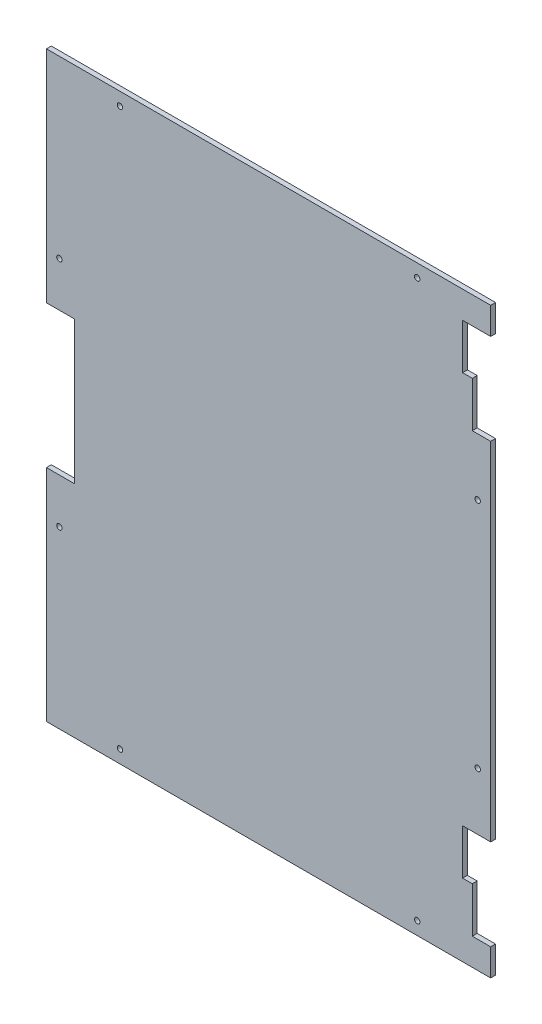
SolidWorks part; units mm, degrees
ref_plane "Front Plane" through (0, 0, 0) normal (0, 0, 1) x (1, 0, 0)
ref_plane "Top Plane" through (0, 0, 0) normal (0, 1, 0) x (1, 0, 0)
ref_plane "Right Plane" through (0, 0, 0) normal (1, 0, 0) x (0, 0, -1)
sketch "Sketch1" plane through (0, 0, 0) normal (0, 0, 1) x (1, 0, 0)
  line L16 (-206.5, 269.5) -> (204.5, 269.5)
  line L32 (-206.5, 269.5) -> (-206.5, 244.5)
  line L33 (-206.5, -269.5) -> (204.5, -269.5)
  line L42 (204.5, 160.5) -> (204.5, -160.5)
  line L43 (-206.5, 0) -> (204.5, 0) construction
  line L49 (204.5, 269.5) -> (204.5, 244.5)
  line L50 (204.5, -244.5) -> (204.5, -269.5)
  line L51 (-1, 269.5) -> (-1, -269.5) construction
  line L57 (-206.5, 160.5) -> (-206.5, 66)
  line L63 (-206.5, -244.5) -> (-206.5, -269.5)
  line L64 (-206.5, -66) -> (-206.5, -160.5)
  line L65 (-206.5, 66) -> (-180.5, 66)
  line L67 (-206.5, -66) -> (-180.5, -66)
  line L68 (-180.5, 66) -> (-180.5, -66)
  line L70 (204.5, 160.5) -> (187.5, 160.5)
  line L71 (187.5, 202.5) -> (187.5, 160.5)
  line L72 (178.5, 202.5) -> (178.5, 244.5)
  line L73 (204.5, 244.5) -> (178.5, 244.5)
  line L74 (178.5, 202.5) -> (187.5, 202.5)
  line L75 (187.5, -244.5) -> (204.5, -244.5)
  line L76 (187.5, -202.5) -> (187.5, -244.5)
  line L77 (178.5, -202.5) -> (187.5, -202.5)
  line L78 (178.5, -160.5) -> (178.5, -202.5)
  line L79 (204.5, -160.5) -> (178.5, -160.5)
  line L80 (-206.5, 160.5) -> (-206.5, 244.5)
  line L81 (-206.5, -160.5) -> (-206.5, -244.5)
  circle A0 centre (136.5, -257.5) radius 2.5
  circle A3 centre (-138.5, -257.5) radius 2.5
  circle A4 centre (-138.5, 257.5) radius 2.5
  circle A7 centre (136.5, 257.5) radius 2.5
  circle A8 centre (-194.5, 107.5) radius 2.5
  circle A9 centre (-194.5, -107.5) radius 2.5
  circle A10 centre (192.5, 107.5) radius 2.5
  circle A11 centre (192.5, -107.5) radius 2.5
  point P17 (185.5, -200.5)
  dimension "D5" = 25
  dimension "D3" = 206.5
  dimension "D7" = 12
  dimension "D10" = 12
  dimension "D11" = 12
  dimension "D6" = 12
  dimension "D8" = 12
  dimension "D18" = 12
  dimension "D21" = 41.5
  dimension "D1" = 539
  dimension "D2" = 411
  dimension "D4" = 269.5
  dimension "D9" = 12
  dimension "D12" = 12
  dimension "D13" = 84
  dimension "D14" = 84
  dimension "D15" = 26
  dimension "D16" = 132
  dimension "D17" = 66
  dimension "D19" = 68
  dimension "D20" = 41.5
  dimension "D22" = 26
  dimension "D23" = 42
  dimension "D24" = 17
  dimension "D25" = 17
  dimension "D26" = 26
  dimension "D27" = 25
extrude "Boss-Extrude1" add sketch "Sketch1" along normal blind 4.5
